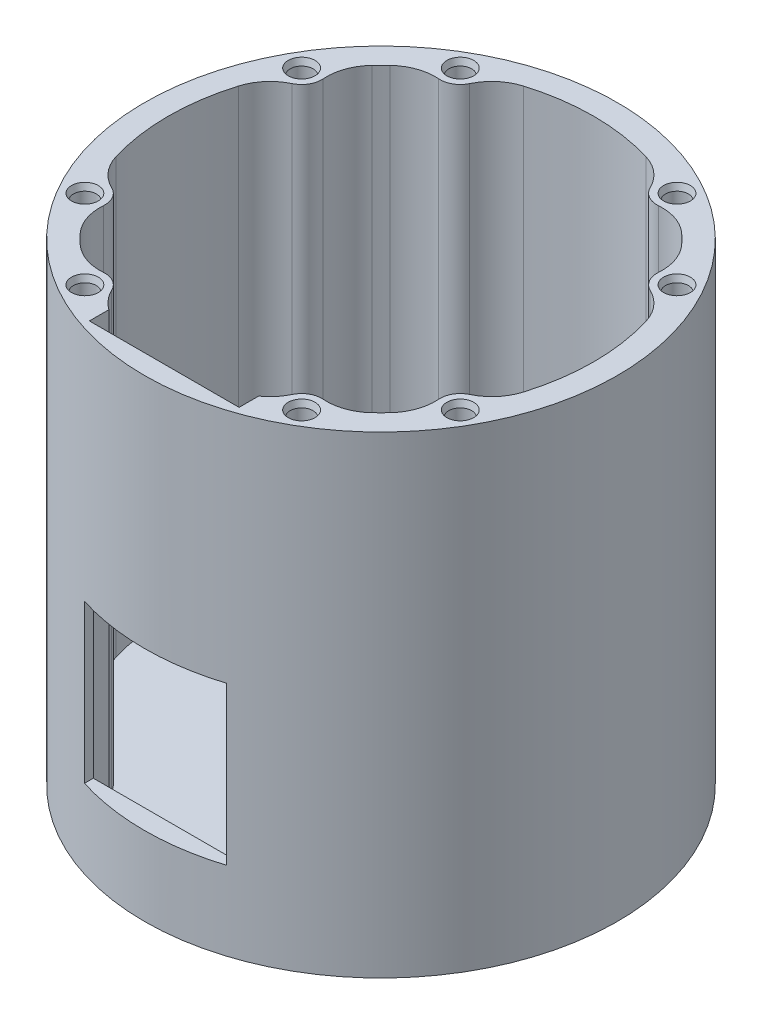
SolidWorks part; units mm, degrees
ref_plane "Ön Düzlem" through (0, 0, 0) normal (0, 0, 1) x (1, 0, 0)
ref_plane "Üst Düzlem" through (0, 0, 0) normal (0, 1, 0) x (1, 0, 0)
ref_plane "Sağ Düzlem" through (0, 0, 0) normal (1, 0, 0) x (0, 0, -1)
sketch "Sketch1" plane through (0, 0, 0) normal (0, 1, 0) x (1, 0, 0)
  circle A0 centre (0, 0) radius 30
  dimension "D1" = 60
extrude "Boss-Extrude1" add sketch "Sketch1" along normal blind 60
sketch "Sketch2" plane through (0, 60, 0) normal (0, 1, 0) x (1, 0, 0)
  line L23 (0, -35.176) -> (0, 35.176) construction
  line L24 (-35.1454, 0) -> (35.1454, 0) construction
  line L25 (0, 0) -> (-17.5855, 30.4589) construction
  arc A0 (-15.5866, 22.0467) -> (-22.0467, 15.5866) centre (0, 0) ccw
  arc A9 (-15.5866, 22.0467) -> (-11.2997, 24.5218) centre (-13.75, 23.8157) ccw
  arc A10 (-24.5218, 11.2997) -> (-22.0467, 15.5866) centre (-23.8157, 13.75) ccw
  arc A11 (-22.0467, -15.5866) -> (-24.5218, -11.2997) centre (-23.8157, -13.75) ccw
  arc A12 (-11.2997, -24.5218) -> (-15.5866, -22.0467) centre (-13.75, -23.8157) ccw
  arc A13 (15.5866, -22.0467) -> (11.2997, -24.5218) centre (13.75, -23.8157) ccw
  arc A14 (24.5218, -11.2997) -> (22.0467, -15.5866) centre (23.8157, -13.75) ccw
  arc A15 (22.0467, 15.5866) -> (24.5218, 11.2997) centre (23.8157, 13.75) ccw
  arc A16 (11.2997, 24.5218) -> (15.5866, 22.0467) centre (13.75, 23.8157) ccw
  arc A19 (-24.5218, 11.2997) -> (-24.5218, -11.2997) centre (0, 0) ccw
  arc A20 (-22.0467, -15.5866) -> (-15.5866, -22.0467) centre (0, 0) ccw
  arc A21 (15.5866, -22.0467) -> (22.0467, -15.5866) centre (0, 0) ccw
  arc A22 (-11.2997, -24.5218) -> (11.2997, -24.5218) centre (0, 0) ccw
  arc A23 (24.5218, -11.2997) -> (24.5218, 11.2997) centre (0, 0) ccw
  arc A24 (22.0467, 15.5866) -> (15.5866, 22.0467) centre (0, 0) ccw
  arc A25 (11.2997, 24.5218) -> (-11.2997, 24.5218) centre (0, 0) ccw
  point P8 (0, 0)
  point P13 (0, 0)
  point P17 (0, 0)
  point P30 (0, 0)
  dimension "D2" = 27.5
  dimension "D6" = 54
  dimension "D1" = 2.55
  dimension "D7" = 30
extrude "Cut-Extrude1" cut sketch "Sketch2" against normal blind 55
fillet "Fillet1" radius 6 16 edges at (-22.0467, 32.5, -15.5866) (-24.5218, 32.5, -11.2997) (-24.5218, 32.5, 11.2997) (-22.0467, 32.5, 15.5866) (-15.5866, 32.5, 22.0467) (-11.2997, 32.5, 24.5218) (11.2997, 32.5, 24.5218) (15.5866, 32.5, 22.0467) (22.0467, 32.5, 15.5866) (24.5218, 32.5, 11.2997) (24.5218, 32.5, -11.2997) (22.0467, 32.5, -15.5866) (15.5866, 32.5, -22.0467) (11.2997, 32.5, -24.5218) (-11.2997, 32.5, -24.5218) (-15.5866, 32.5, -22.0467)
sketch "Sketch4" plane through (0, 60, 0) normal (0, 1, 0) x (1, 0, 0)
  line L0 (-9.5, -27.5) -> (9.5, -27.5)
  line L1 (-9.5, -27.5) -> (-9.5, -24.5)
  line L2 (-9.5, -24.5) -> (9.5, -24.5)
  line L3 (9.5, -24.5) -> (9.5, -27.5)
  point P0 (0, -27.5)
  point P5 (0, -27.5)
  dimension "D1" = 27.5
  dimension "D2" = 19
  dimension "D3" = 3
extrude "Cut-Extrude3" cut sketch "Sketch4" against normal blind 55
sketch "Sketch7" plane through (0, 0, 0) normal (0, 0, 1) x (1, 0, 0)
  line L1 (-9, 10) -> (9, 10)
  line L2 (-9, 10) -> (-9, 30)
  line L3 (-9, 30) -> (9, 30)
  line L4 (9, 10) -> (9, 30)
  line L5 (-9, 10) -> (9, 30) construction
  line L6 (-9, 30) -> (9, 10) construction
  point P0 (0, 20)
  dimension "D1" = 18
  dimension "D2" = 10
  dimension "D3" = 20
extrude "Cut-Extrude5" cut sketch "Sketch7" along normal up to next
sketch "Sketch6" plane through (0, 60, 0) normal (0, 1, 0) x (1, 0, 0)
  point P0 (-13.75, 23.8157)
  point P1 (-23.8157, 13.75)
  point P3 (-23.8157, -13.75)
  point P4 (-13.75, -23.8157)
  point P6 (13.75, -23.8157)
  point P7 (23.8157, -13.75)
  point P9 (23.8157, 13.75)
  point P10 (13.75, 23.8157)
hole_wizard "HoleWzd1" positions "Sketch6" profile "Sketch8" legacy
sketch "Sketch8" plane through (-13.75, 60, -23.8157) normal (1, 0, 0) x (0, 0, 1)
  line L0 (0, 0) -> (0, 5)
  line L1 (0, 5) -> (1.45, 5)
  line L2 (1.45, 5) -> (1.45, 0.8002)
  line L3 (1.45, 0.8002) -> (1.7, 0)
  line L4 (1.7, 0) -> (0, 0)
  line L5 (0, -6.4453) -> (0, 115.525) construction
  line L6 (-1.45, 0.8002) -> (-1.7, 0) construction
  dimension "Diameter" = 2.9
  dimension "Depth" = 5
  dimension "C-Sink Angle" = 34.7
  dimension "C-Sink Diameter" = 3.4
